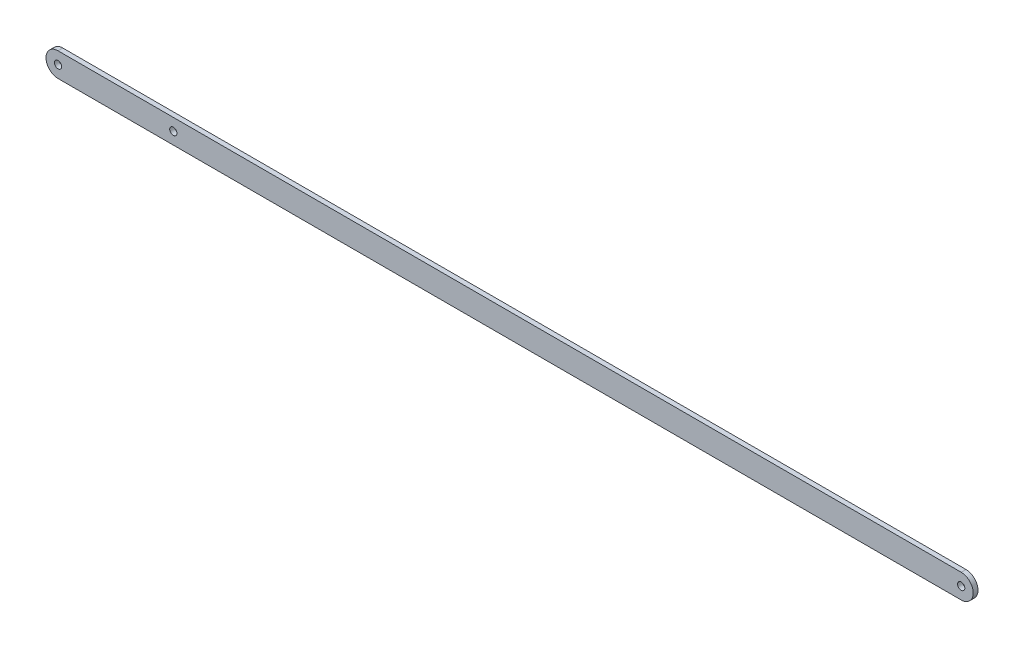
SolidWorks part; units mm, degrees
material "Plain Carbon Steel"
ref_plane "Front Plane" through (0, 0, 0) normal (0, 0, 1) x (1, 0, 0)
ref_plane "Top Plane" through (0, 0, 0) normal (0, 1, 0) x (1, 0, 0)
ref_plane "Right Plane" through (0, 0, 0) normal (1, 0, 0) x (0, 0, -1)
sketch "Sketch1" plane through (0, 0, 0) normal (0, 0, 1) x (1, 0, 0)
  line L0 (596.9, 0) -> (-596.9, 0) construction
  line L1 (3.4925, 0) -> (-3.4925, 0) construction
  line L2 (596.9, -15.875) -> (-596.9, -15.875)
  line L3 (596.9, 15.875) -> (-596.9, 15.875)
  arc A0 (596.9, -15.875) -> (596.9, 15.875) centre (596.9, 0) ccw
  arc A1 (-596.9, 15.875) -> (-596.9, -15.875) centre (-596.9, 0) ccw
  circle A2 centre (-596.9, 0) radius 4.7625
  circle A3 centre (596.9, 0) radius 4.7625
  point P5 (0, 0)
  dimension "D3" = 9.525
  dimension "D4" = 9.525
  dimension "D1" = 31.75
  dimension "D2" = 1193.8
extrude "Boss-Extrude1" add sketch "Sketch1" along normal mid plane 6.35
sketch "Sketch2" plane through (0, 0, 3.175) normal (0, 0, 1) x (1, 0, 0)
  line L0 (3.4925, 0) -> (-3.4925, 0) construction
  circle A0 centre (-444.5, 0) radius 4.7625
  circle A1 centre (-596.9, 0) radius 4.7625 construction
  point P2 (0, 0)
  dimension "D1" = 152.4
extrude "Cut-Extrude1" cut sketch "Sketch2" against normal through all
